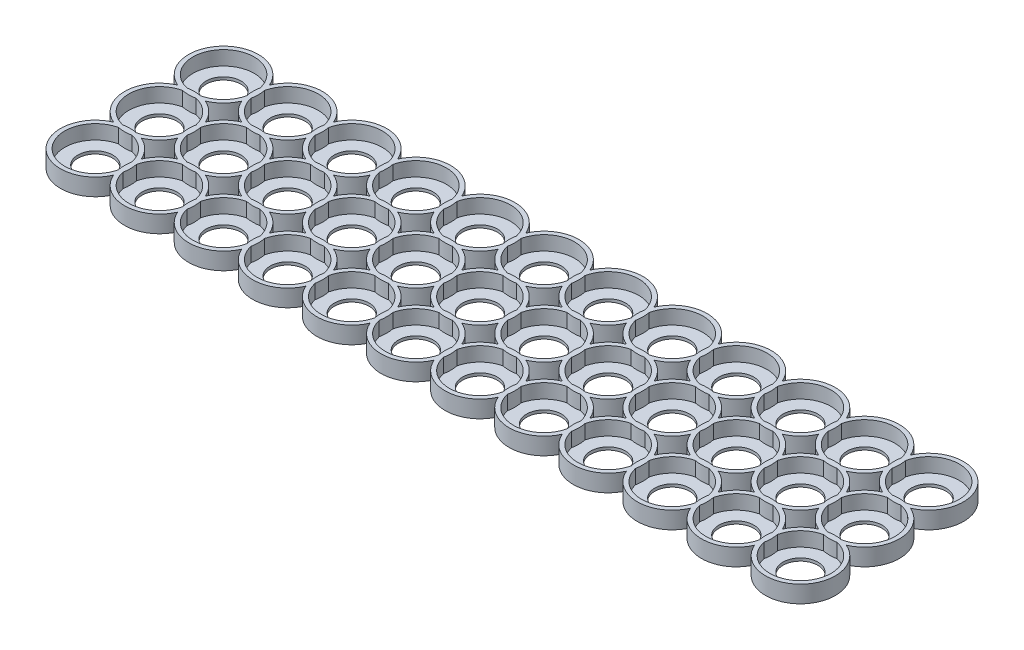
SolidWorks part; units mm, degrees
ref_plane "Front Plane" through (0, 0, 0) normal (0, 0, 1) x (1, 0, 0)
ref_plane "Top Plane" through (0, 0, 0) normal (0, 1, 0) x (1, 0, 0)
ref_plane "Right Plane" through (0, 0, 0) normal (1, 0, 0) x (0, 0, -1)
sketch "Sketch1" plane through (0, 0, 0) normal (1, 0, 0) x (0, 0, -1)
  line L0 (0, 27.0772) -> (0, -22.0037) construction
  line L1 (-12.25, 3) -> (-12.25, -3)
  line L2 (-12.25, -3) -> (-6.125, -3)
  line L3 (-6.125, -3) -> (-6.125, -2)
  line L4 (-6.125, -2) -> (-10.75, -2)
  line L5 (-10.75, -2) -> (-10.75, 3)
  line L6 (-10.75, 3) -> (-12.25, 3)
  point P5 (-12.25, 0)
  dimension "D1" = 6
  dimension "D2" = 1
  dimension "D3" = 21.5
  dimension "D4" = 12.25
  dimension "D5" = 1.5
revolve "Revolve1" add sketch "Sketch1" angle 360 about L0
sketch "Sketch2" plane through (0, -3, 0) normal (0, -1, 0) x (1, 0, 0)
  line L0 (0, 12.1827) -> (0, -11.4982) construction
pattern_linear "LPattern1" count 3 spacing 22.5 along (0, 0, -1) of "Revolve1"
sketch "Sketch3" plane through (0, -3, 0) normal (0, -1, 0) x (1, 0, 0)
  line L0 (-17.2986, 0) -> (17.8169, 0) construction
pattern_linear "LPattern2" count 12 spacing 22.5 along (1, 0, 0) of "Revolve1", "LPattern1"
